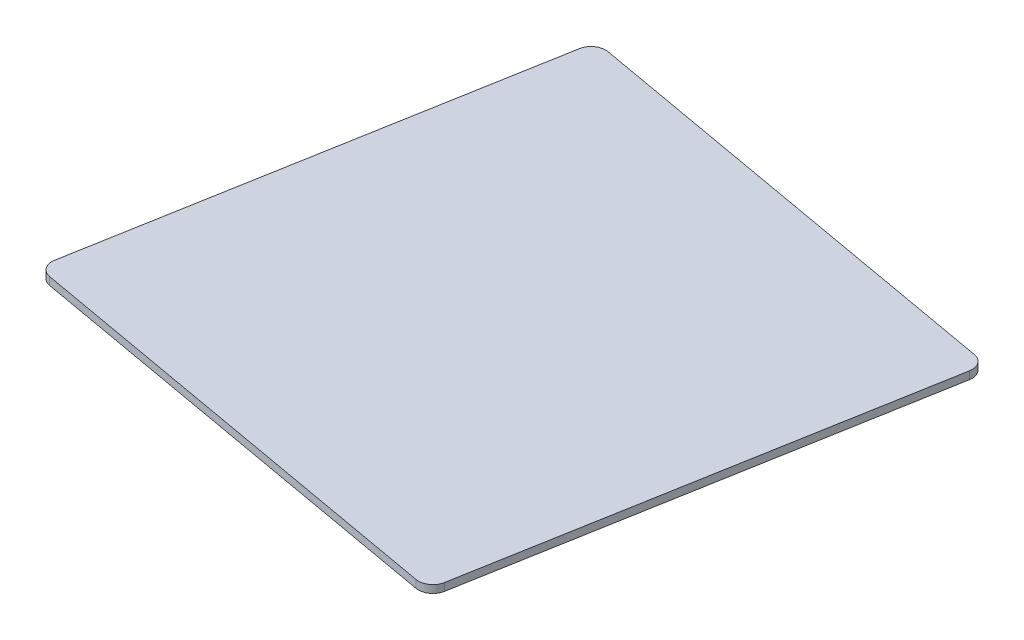
SolidWorks part; units mm, degrees
ref_plane "Front Plane" through (0, 0, 0) normal (0, 0, 1) x (1, 0, 0)
ref_plane "Top Plane" through (0, 0, 0) normal (0, 1, 0) x (1, 0, 0)
ref_plane "Right Plane" through (0, 0, 0) normal (1, 0, 0) x (0, 0, -1)
sketch "Sketch1" plane through (0, -27.7713, 0) normal (0, -1, 0) x (-1, 0, 0)
  line L4 (350.5099, -192.8902) -> (257.9579, -209.3256)
  line L5 (255.5287, -212.8039) -> (271.9641, -305.356)
  line L6 (275.4424, -307.7852) -> (367.9944, -291.3498)
  line L7 (370.4237, -287.8715) -> (353.9883, -195.3194)
  line L8 (350.5099, -192.8902) -> (257.9579, -209.3256)
  line L9 (255.5287, -212.8039) -> (271.9641, -305.356)
  line L10 (275.4424, -307.7852) -> (367.9944, -291.3498)
  line L11 (370.4237, -287.8715) -> (353.9883, -195.3194)
  arc A4 (257.9579, -209.3256) -> (255.5287, -212.8039) centre (258.4825, -212.2794) ccw
  arc A5 (271.9641, -305.356) -> (275.4424, -307.7852) centre (274.9179, -304.8314) ccw
  arc A6 (367.9944, -291.3498) -> (370.4237, -287.8715) centre (367.4699, -288.396) ccw
  arc A7 (353.9883, -195.3194) -> (350.5099, -192.8902) centre (351.0345, -195.844) ccw
  arc A8 (257.9579, -209.3256) -> (255.5287, -212.8039) centre (258.4825, -212.2794) ccw
  arc A9 (271.9641, -305.356) -> (275.4424, -307.7852) centre (274.9179, -304.8314) ccw
  arc A10 (367.9944, -291.3498) -> (370.4237, -287.8715) centre (367.4699, -288.396) ccw
  arc A11 (353.9883, -195.3194) -> (350.5099, -192.8902) centre (351.0345, -195.844) ccw
  dimension "D1" = 0
extrude "Boss-Extrude1" add sketch "Sketch1" along normal blind 1.6
